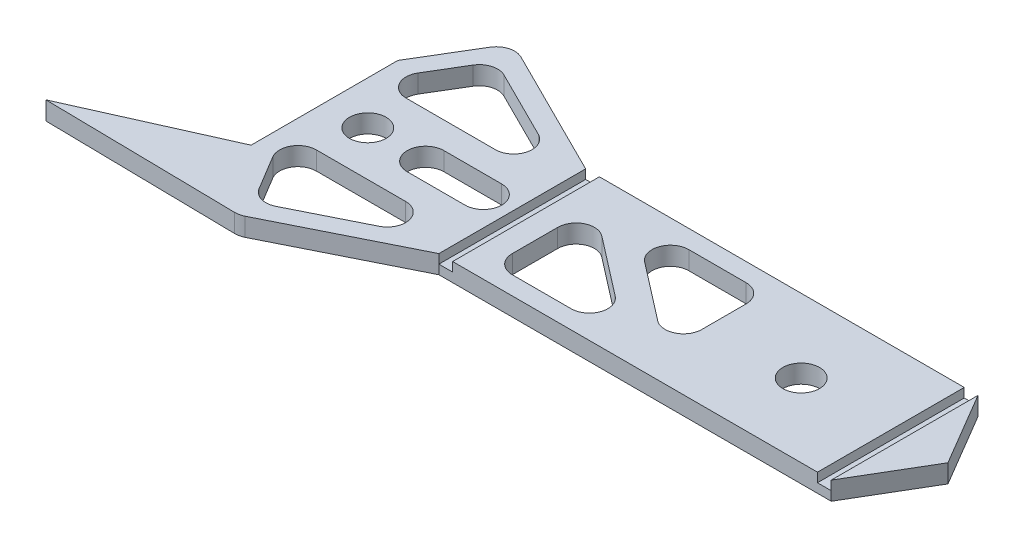
SolidWorks part; units mm, degrees
material "AISI 1020"
ref_plane "Alzado" through (0, 0, 0) normal (0, 0, 1) x (1, 0, 0)
ref_plane "Planta" through (0, 0, 0) normal (0, 1, 0) x (1, 0, 0)
ref_plane "Vista lateral" through (0, 0, 0) normal (1, 0, 0) x (0, 0, -1)
sketch "Croquis1" plane through (0, 0, 0) normal (0, 1, 0) x (1, 0, 0)
  line L0 (35.8, -25.4) -> (50.8, 0)
  line L3 (-43.9941, -25.4) -> (35.8, -25.4) construction
  line L4 (35.8, 25.4) -> (35.8, -25.4) construction
  line L5 (50.8, 0) -> (35.8, 25.4)
  line L6 (0, 0) -> (35.8, 0) construction
  line L11 (0, 0) -> (0, -19.05) construction
  line L12 (-19.05, 19.05) -> (19.05, 19.05) construction
  line L13 (-19.05, 19.05) -> (-19.05, -19.05) construction
  line L14 (-19.05, -19.05) -> (19.05, -19.05) construction
  line L15 (19.05, 19.05) -> (19.05, -19.05) construction
  line L16 (35.8, 25.4) -> (-100, 25.4)
  line L20 (-100, -25.4) -> (35.8, -25.4)
  line L21 (0, 0) -> (-165, 0) construction
  line L24 (-3.1555, -50.7019) -> (59.478, -54.5999) construction
  line L38 (-100, -25.4) -> (-100, 25.4) construction
  line L41 (-100, -25.4) -> (-144.7468, -47.7317)
  line L42 (-153.0248, -45.3215) -> (-165, -25.4) construction
  line L43 (-165, -25.4) -> (-165, 25.4)
  line L44 (-165, 25.4) -> (-153.0248, 45.3215)
  line L45 (-144.7468, 47.7317) -> (-100, 25.4)
  line L46 (-150, -50.3534) -> (-150, 50.3534) construction
  line L47 (-165, 25.4) -> (-100, 25.4) construction
  line L48 (-100, -25.4) -> (-165, -25.4) construction
  line L49 (-165, -25.4) -> (-214.0738, -47.3169)
  line L50 (-214.0738, -47.3169) -> (-147.6859, -48.3992)
  line L51 (-173.3511, 48.4) -> (-113.9016, 48.4) construction
  line L52 (-118.5451, 27.5584) -> (-142.3292, 39.4283)
  line L53 (-150.6072, 37.0181) -> (-157.7424, 25.1482)
  line L54 (-152.3, 15.5267) -> (-121.3807, 15.5267)
  line L55 (-177.7394, 6.35) -> (-121.5741, 6.35) construction
  line L56 (-158.65, 48.4) -> (-158.65, -3.791) construction
  line L57 (-118.5451, -27.5584) -> (-142.3292, -39.4283)
  line L58 (-150.6072, -37.0181) -> (-157.7424, -25.1482)
  line L59 (-152.3, -15.5267) -> (-121.3807, -15.5267)
  line L60 (-130, 6.35) -> (-110, 6.35)
  line L61 (-110, -6.35) -> (-130, -6.35)
  line L62 (-56.7008, -7.6756) -> (-77.0669, 8.0642)
  line L63 (-57.9633, 19.05) -> (-38.1, 19.05)
  line L64 (-87.3, 3.0398) -> (-87.3, -12.7)
  line L65 (-80.95, -19.05) -> (-60.5839, -19.05)
  line L66 (-31.75, 12.7) -> (-31.75, -2.6513)
  line L67 (-61.8464, 7.6756) -> (-41.9831, -7.6756)
  line L68 (-41.9831, -7.6756) -> (-56.7008, -7.6756) construction
  circle A0 centre (0, 0) radius 6.35
  circle A1 centre (0, 0) radius 50.8 construction
  circle A11 centre (-150, 0) radius 6.35
  circle A12 centre (-150, 0) radius 44.45 construction
  arc A13 (-144.7468, -47.7317) -> (-153.0248, -45.3215) centre (-147.5824, -42.05) cw construction
  arc A14 (-153.0248, 45.3215) -> (-144.7468, 47.7317) centre (-147.5824, 42.05) cw
  arc A15 (-147.6859, -48.3992) -> (-144.7468, -47.7317) centre (-147.5824, -42.05) ccw
  arc A16 (-118.5451, 27.5584) -> (-121.3807, 15.5267) centre (-121.3807, 21.8767) cw
  arc A17 (-157.7424, 25.1482) -> (-152.3, 15.5267) centre (-152.3, 21.8767) ccw
  arc A18 (-142.3292, 39.4283) -> (-150.6072, 37.0181) centre (-145.1648, 33.7466) ccw
  arc A19 (-118.5451, -27.5584) -> (-121.3807, -15.5267) centre (-121.3807, -21.8767) ccw
  arc A20 (-142.3292, -39.4283) -> (-150.6072, -37.0181) centre (-145.1648, -33.7466) cw
  arc A21 (-157.7424, -25.1482) -> (-152.3, -15.5267) centre (-152.3, -21.8767) cw
  arc A22 (-130, 6.35) -> (-130, -6.35) centre (-130, 0) ccw
  arc A23 (-110, -6.35) -> (-110, 6.35) centre (-110, 0) ccw
  arc A25 (-38.1, 19.05) -> (-31.75, 12.7) centre (-38.1, 12.7) cw
  arc A27 (-87.3, -12.7) -> (-80.95, -19.05) centre (-80.95, -12.7) ccw
  arc A28 (-57.9633, 19.05) -> (-61.8464, 7.6756) centre (-57.9633, 12.7) ccw
  arc A29 (-31.75, -2.6513) -> (-41.9831, -7.6756) centre (-38.1, -2.6513) cw
  arc A30 (-60.5839, -19.05) -> (-56.7008, -7.6756) centre (-60.5839, -12.7) ccw
  arc A31 (-87.3, 3.0398) -> (-77.0669, 8.0642) centre (-80.95, 3.0398) cw
  point P19 (19.05, 0)
  point P20 (-165, 0)
  point P84 (0, 0)
  dimension "D1" = 12.7
  dimension "D2" = 101.6
  dimension "D7" = 6.35
  dimension "D10" = 23
  dimension "D11" = 25
  dimension "D9" = 15
  dimension "D15" = 20
  dimension "D3" = 50
  dimension "D4" = 88.9
  dimension "D12" = 12.7
  dimension "D13" = 6.35
  dimension "D18" = 6.35
  dimension "D21" = 6.35
  dimension "D22" = 9
  dimension "D24" = 6.35
  dimension "D25" = 6.35
  dimension "D5" = 50.8
  dimension "D6" = 15
  dimension "D8" = 38.1
  dimension "D14" = 6.35
  dimension "D16" = 10
  dimension "D17" = 100
  dimension "D19" = 12.7
  dimension "D20" = 12.7
  dimension "D23" = 17.7244
extrude "Saliente-Extruir1" add sketch "Croquis1" along normal blind 6.35
sketch "Croquis4" plane through (0, 6.35, 0) normal (0, 1, 0) x (1, 0, 0)
  line L0 (-100, -25.4) -> (35.8, -25.4) construction
  line L1 (-95.2375, -25.4) -> (-100, -25.4)
  line L2 (-95.2375, -25.4) -> (-95.2375, 25.4)
  line L3 (-95.2375, 25.4) -> (-100, 25.4)
  line L4 (-100, -25.4) -> (-100, 25.4)
  line L5 (35.8, 25.4) -> (-100, 25.4) construction
  line L6 (35.8, -25.4) -> (31.0375, -25.4)
  line L7 (35.8, -25.4) -> (35.8, 25.4)
  line L8 (35.8, 25.4) -> (31.0375, 25.4)
  line L9 (31.0375, -25.4) -> (31.0375, 25.4)
  dimension "D1" = 4.7625
extrude "Cortar-Extruir1" cut sketch "Croquis4" against normal blind 3.175
